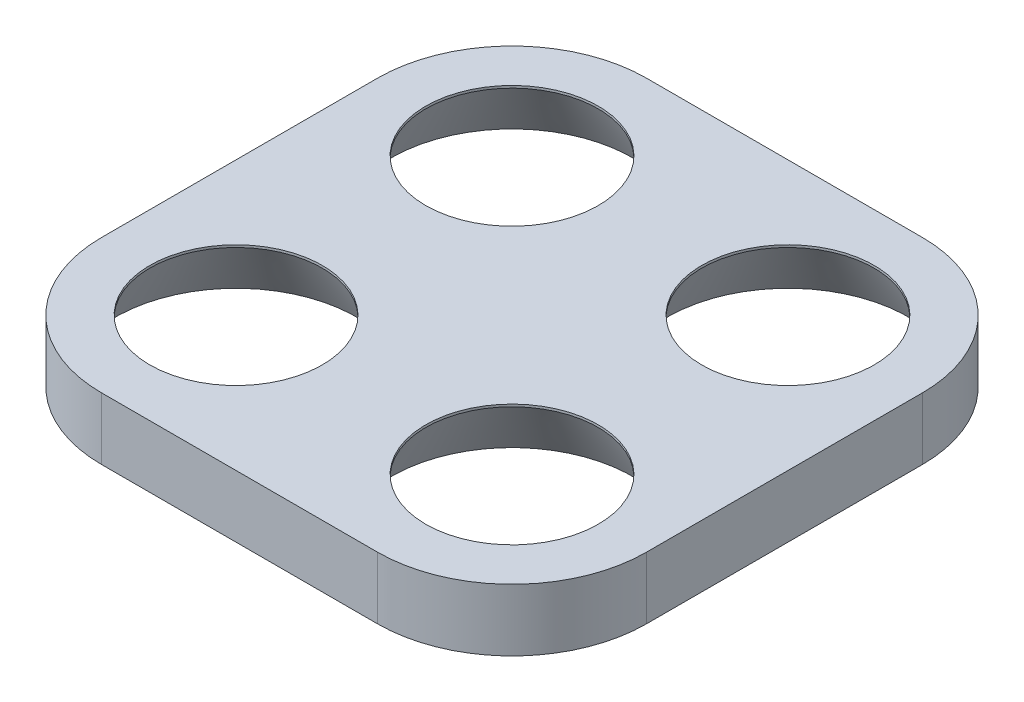
SolidWorks part; units mm, degrees
ref_plane "Front Plane" through (0, 0, 0) normal (0, 0, 1) x (1, 0, 0)
ref_plane "Top Plane" through (0, 0, 0) normal (0, 1, 0) x (1, 0, 0)
ref_plane "Right Plane" through (0, 0, 0) normal (1, 0, 0) x (0, 0, -1)
sketch "Sketch1" plane through (0, 0, 0) normal (0, 1, 0) x (1, 0, 0)
  line L1 (7.9, -7.9) -> (-7.9, -7.9)
  line L2 (7.9, -7.9) -> (7.9, 7.9)
  line L3 (7.9, 7.9) -> (-7.9, 7.9)
  line L4 (-7.9, -7.9) -> (-7.9, 7.9)
  line L5 (7.9, -7.9) -> (-7.9, 7.9) construction
  line L6 (7.9, 7.9) -> (-7.9, -7.9) construction
  point P0 (0, 0)
  dimension "D1" = 15.8
extrude "Boss-Extrude1" add sketch "Sketch1" along normal blind 1.8
sketch "Sketch2" plane through (0, 1.8, 0) normal (0, 1, 0) x (1, 0, 0)
  line L1 (4, -4) -> (-4, -4) construction
  line L2 (4, -4) -> (4, 4) construction
  line L3 (4, 4) -> (-4, 4) construction
  line L4 (-4, -4) -> (-4, 4) construction
  line L5 (4, -4) -> (-4, 4) construction
  line L6 (4, 4) -> (-4, -4) construction
  circle A0 centre (-4, 4) radius 2.5
  circle A1 centre (4, 4) radius 2.5
  circle A2 centre (4, -4) radius 2.5
  circle A3 centre (-4, -4) radius 2.5
  point P0 (0, 0)
  dimension "D2" = 5
  dimension "D1" = 8
extrude "Cut-Extrude1" cut sketch "Sketch2" against normal up to next
fillet "Fillet1" radius 3.9 4 edges at (-7.9, 0.9, 7.9) (7.9, 0.9, 7.9) (7.9, 0.9, -7.9) (-7.9, 0.9, -7.9)
chamfer "Chamfer1" distance 1 angle 60 4 edges at (4, 0, -1.5) (4, 0, 6.5) (-4, 0, -1.5) (-4, 0, 6.5)
